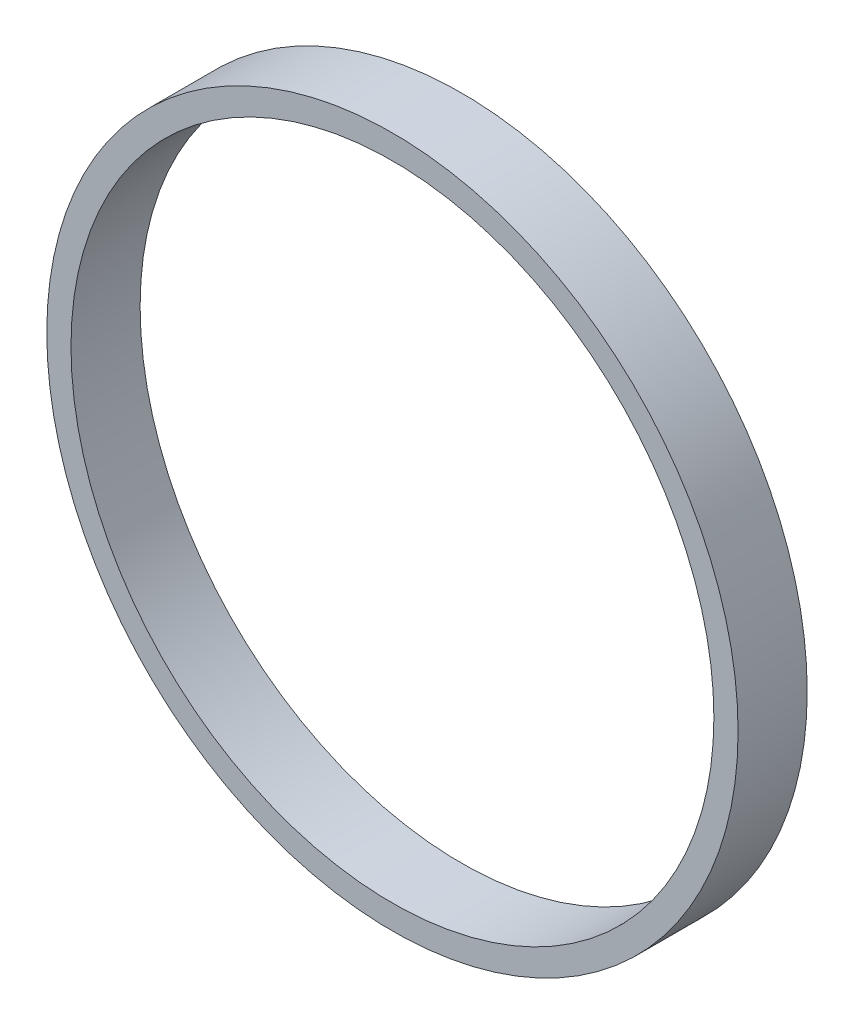
SolidWorks part; units mm, degrees
material "A-玻璃纤维"
ref_plane "前视基准面" through (0, 0, 0) normal (0, 0, 1) x (1, 0, 0)
ref_plane "上视基准面" through (0, 0, 0) normal (0, 1, 0) x (1, 0, 0)
ref_plane "右视基准面" through (0, 0, 0) normal (1, 0, 0) x (0, 0, -1)
sketch "草图1" plane through (0, 0, 0) normal (0, 0, 1) x (1, 0, 0)
  circle A0 centre (0, 0) radius 18.6
  circle A1 centre (0, 0) radius 20
  dimension "D1" = 37.2
  dimension "D2" = 40
extrude "凸台-拉伸1" add sketch "草图1" along normal blind 4
